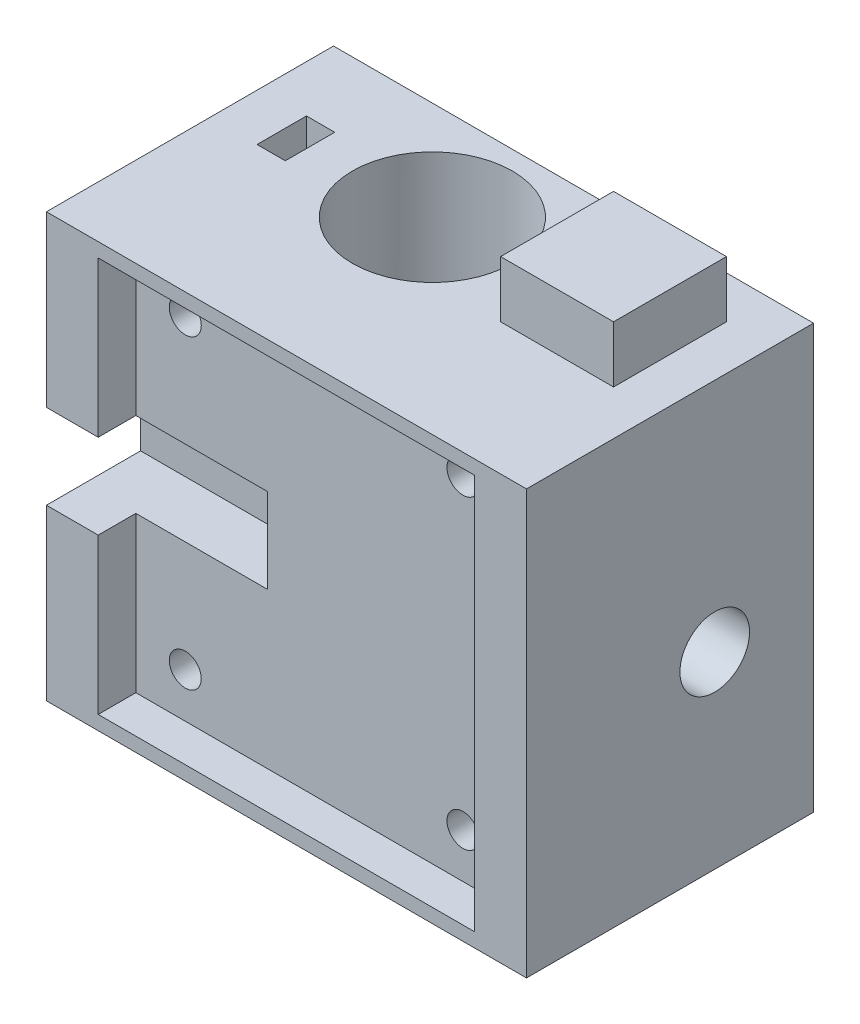
SolidWorks part; units mm, degrees
ref_plane "Front Plane" through (0, 0, 0) normal (0, 0, 1) x (1, 0, 0)
ref_plane "Top Plane" through (0, 0, 0) normal (0, 1, 0) x (1, 0, 0)
ref_plane "Right Plane" through (0, 0, 0) normal (1, 0, 0) x (0, 0, -1)
sketch "Base" plane through (0, 0, 0) normal (0, 1, 0) x (1, 0, 0)
  line L0 (0, 0) -> (0, -20) construction
  circle A0 centre (0, 0) radius 10.5
  dimension "D1" = 21
extrude "Cutlure Tube Housing" add sketch "Base" along normal blind 45
sketch "Sketch1" plane through (0, 45, 0) normal (0, 1, 0) x (1, 0, 0)
  line L1 (-21, 10.5) -> (30, 10.5)
  line L2 (-21, 10.5) -> (-21, -20)
  line L3 (-21, -20) -> (30, -20)
  line L4 (30, 10.5) -> (30, -20)
  circle A1 centre (0, 0) radius 10.5 construction
  dimension "D1" = 21
  dimension "D2" = 30
  dimension "D3" = 20
extrude "Detector+Laser Housing" add sketch "Sketch1" against normal up to surface (45 mm away) up to face at (0, 0, 10.5)
sketch "Culture Slot" plane through (0, 45, 0) normal (0, 1, 0) x (1, 0, 0)
  circle A0 centre (0, 0) radius 8.5
  dimension "D1" = 17
extrude "Culture Tube Slot" cut sketch "Culture Slot" against normal offset from surface (40 mm away) 5 up to face at (4.5, 0, 4.75)
sketch "Sketch3" plane through (0, 0, 0) normal (1, 0, 0) x (0, 0, -1)
  circle A0 centre (0, 20) radius 3.7
  dimension "D1" = 7.4
  dimension "D2" = 20
extrude "Laser Port" cut sketch "Sketch3" against normal offset from surface 5 and the other way through all up to face at (-21, 22.5, 4.75)
sketch "Sketch4" plane through (0, 45, 0) normal (0, 1, 0) x (1, 0, 0)
  line L0 (0, 0) -> (-21, 0) construction
  line L1 (-16, 2.625) -> (-13, 2.625)
  line L2 (-16, 2.625) -> (-16, -2.625)
  line L3 (-16, -2.625) -> (-13, -2.625)
  line L4 (-13, 2.625) -> (-13, -2.625)
  line L5 (-21, 10.5) -> (-21, -20) construction
  point P4 (-16, 0)
  dimension "D1" = 5.25
  dimension "D2" = 3
  dimension "D3" = 5
extrude "Cut-Extrude3" cut sketch "Sketch4" against normal up to next
hole_wizard "LED display Screw Holes" positions "Sketch12" profile "Sketch13" legacy
sketch "Sketch12" plane through (0, 0, 20) normal (0, 0, 1) x (1, 0, 0)
  line L2 (4.5, 45) -> (4.5, 0) construction
  line L3 (-21, 45) -> (30, 45) construction
  line L4 (30, 0) -> (-21, 0) construction
  line L6 (30, 22.5) -> (-21, 22.5) construction
  line L7 (30, 0) -> (30, 45) construction
  line L8 (-21, 0) -> (-21, 45) construction
  point P0 (-10.25, 38.75)
  point P2 (-10.25, 6.25)
  point P4 (19.25, 38.75)
  point P6 (19.25, 6.25)
  point P42 (0, 0)
  dimension "D1" = 32.5
  dimension "D2" = 29.5
sketch "Sketch13" plane through (-10.25, 38.75, 20) normal (1, 0, 0) x (0, -1, 0)
  line L0 (0, 0) -> (0, 20)
  line L1 (0, 20) -> (1.7, 20)
  line L2 (1.7, 20) -> (1.7, 0)
  line L3 (1.7, 0) -> (0, 0)
  line L4 (0, 110) -> (0, -10) construction
  dimension "Diameter" = 3.4
  dimension "Depth" = 20
sketch "Sketch14" plane through (0, 0, 20) normal (0, 0, 1) x (1, 0, 0)
  line L0 (-10.25, 38.75) -> (19.25, 6.25) construction
  line L1 (-15.5, 43.5) -> (24.5, 43.5)
  line L2 (-15.5, 43.5) -> (-15.5, 1.5)
  line L3 (-15.5, 1.5) -> (24.5, 1.5)
  line L4 (24.5, 43.5) -> (24.5, 1.5)
  point P8 (4.5, 22.5)
  point P9 (24.5, 22.5)
  point P10 (4.5, 43.5)
  dimension "D1" = 40
  dimension "D2" = 42
extrude "Cut-Extrude4" cut sketch "Sketch14" against normal blind 4
sketch "Sketch16" plane through (0, 0, 20) normal (0, 0, 1) x (1, 0, 0)
  line L0 (-15.5, 43.5) -> (-15.5, 1.5) construction
  line L1 (-1.5, 27) -> (-21, 27)
  line L2 (-1.5, 27) -> (-1.5, 18)
  line L3 (-1.5, 18) -> (-21, 18)
  line L4 (-21, 27) -> (-21, 18)
  line L6 (-21, 0) -> (-21, 45) construction
  line L7 (-15.5, 43.5) -> (-15.5, 1.5) construction
  point P8 (-21, 22.5)
  point P9 (30, 28.6317)
  point P10 (-15.5, 22.5)
  dimension "D1" = 14
  dimension "D2" = 9
extrude "Cut-Extrude6" cut sketch "Sketch16" against normal blind 10
sketch "Sketch17" plane through (0, 45, 0) normal (0, 1, 0) x (1, 0, 0)
  line L0 (8.5, 0) -> (30, 0) construction
  line L1 (13.25, 6) -> (25.25, 6)
  line L2 (13.25, 6) -> (13.25, -6)
  line L3 (13.25, -6) -> (25.25, -6)
  line L4 (25.25, 6) -> (25.25, -6)
  line L5 (30, -20) -> (30, 10.5) construction
  circle A0 centre (0, 0) radius 8.5 construction
  circle A1 centre (0, 0) radius 8.5 construction
  point P13 (19.25, 0)
  point P14 (19.25, 6)
  dimension "D1" = 12
  dimension "D2" = 12
extrude "Boss-Extrude3" add sketch "Sketch17" along normal blind 6
